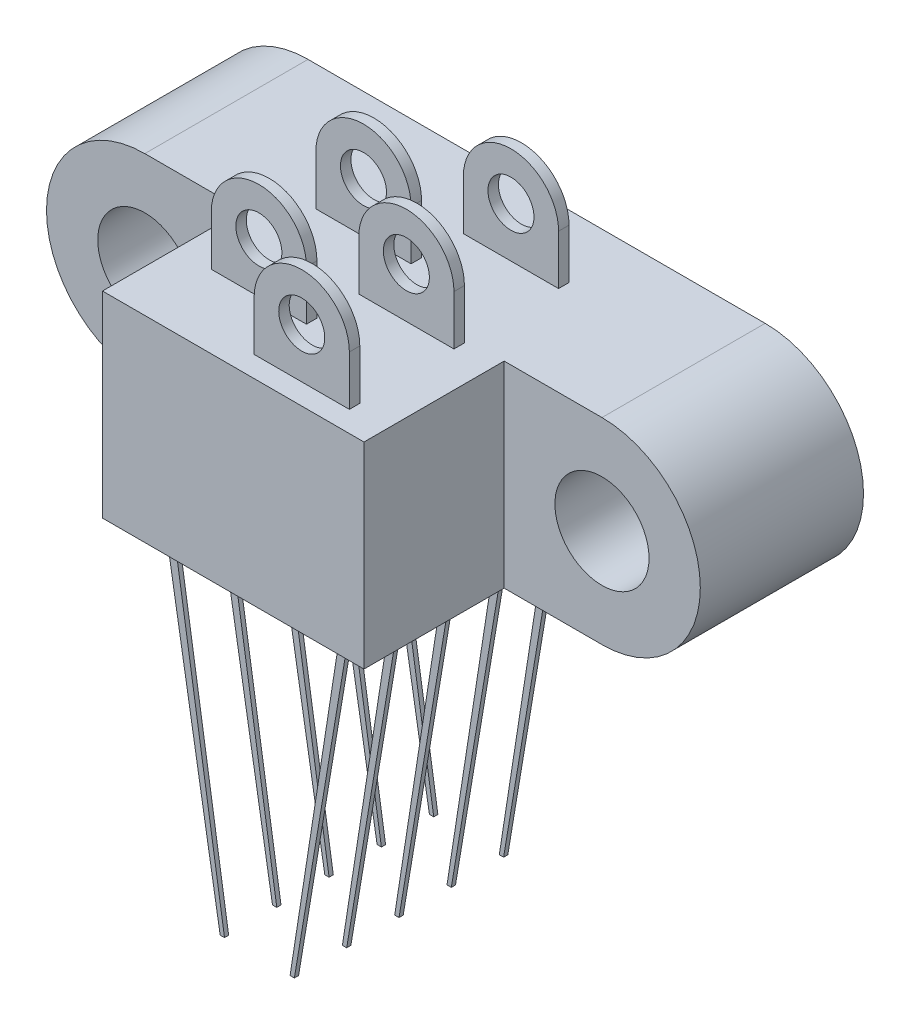
SolidWorks part; units mm, degrees
ref_plane "Front Plane" through (0, 0, 0) normal (0, 0, 1) x (1, 0, 0)
ref_plane "Top Plane" through (0, 0, 0) normal (0, 1, 0) x (1, 0, 0)
ref_plane "Right Plane" through (0, 0, 0) normal (1, 0, 0) x (0, 0, -1)
sketch "Sketch1" plane through (0, 0, 0) normal (0, 0, 1) x (1, 0, 0)
  line L0 (-5.5499, 2.3876) -> (5.5499, 2.3876)
  line L1 (-5.5499, -2.3876) -> (5.5499, -2.3876)
  circle A0 centre (-5.5499, 0) radius 1.143
  circle A1 centre (5.5499, 0) radius 1.143
  arc A2 (-5.5499, 2.3876) -> (-5.5499, -2.3876) centre (-5.5499, 0) ccw
  arc A3 (5.5499, -2.3876) -> (5.5499, 2.3876) centre (5.5499, 0) ccw
  dimension "D1" = 11.0998
  dimension "D2" = 5.5499
extrude "Boss-Extrude1" add sketch "Sketch1" along normal blind 3.9624
sketch "Sketch2" plane through (0, 0, 3.9624) normal (0, 0, 1) x (1, 0, 0)
  line L0 (0, 0) -> (0, 9.5761) construction
  line L1 (-3.175, 2.3876) -> (-3.175, -2.3876)
  line L2 (3.175, 2.3876) -> (3.175, -2.3876)
  line L3 (-3.175, 2.3876) -> (3.175, 2.3876)
  line L5 (-3.175, -2.3876) -> (3.175, -2.3876)
  dimension "D1" = 6.35
  dimension "D2" = 3.175
extrude "Boss-Extrude2" add sketch "Sketch2" along normal blind 3.4036
sketch3d "3DSketch1" plane through (0, 0, 0) normal (0, 0, 1) x (1, 0, 0)
  dimension "D1" = 1.651
  dimension "D2" = 1.27
  dimension "D3" = 2.54
  dimension "D4" = 3.81
  dimension "D5" = 5.08
sketch "Sketch3" plane through (0, 0, 1.651) normal (0, 0, -1) x (-1, 0, 0)
  line L0 (-1.1557, 4.7498) -> (-1.1557, 0.3247) construction
  line L1 (-5.5499, 2.3876) -> (5.5499, 2.3876) construction
  line L2 (0, 2.3876) -> (0, 3.5941) construction
  line L5 (-2.3114, 3.5941) -> (-2.3114, 2.3876)
  line L8 (0, 3.5941) -> (0, 2.3876)
  line L9 (0, 4.7845) -> (0, 9.569) construction
  line L11 (0, 2.3876) -> (-2.3114, 2.3876)
  arc A1 (0, 3.5941) -> (-2.3114, 3.5941) centre (-1.1557, 3.5941) ccw
  circle A2 centre (-1.1557, 3.5941) radius 0.5588
  dimension "D2" = 0
extrude "Boss-Extrude3" add sketch "Sketch3" along normal blind 0.127 and the other way blind 0.127
sketch "Sketch4" plane through (0, 0, 2.921) normal (0, 0, -1) x (-1, 0, 0)
  line L3 (0, 2.3876) -> (0, 3.5941) construction
  line L4 (2.3114, 3.5941) -> (2.3114, 2.3876)
  line L5 (2.3114, 2.3876) -> (0, 2.3876)
  line L6 (-2.3114, 3.5941) -> (-2.3114, 2.3876)
  line L7 (-2.3114, 2.3876) -> (0, 2.3876)
  line L8 (0, 2.3876) -> (0, 3.5941)
  line L9 (-2.3114, 3.5941) -> (-2.3114, 2.3876) construction
  line L10 (-2.3114, 2.3876) -> (2.3114, 2.3876) construction
  line L11 (0, 2.3876) -> (0, 3.5941)
  arc A2 (0, 3.5941) -> (-2.3114, 3.5941) centre (-1.1557, 3.5941) ccw
  arc A3 (0, 3.5941) -> (-2.3114, 3.5941) centre (-1.1557, 3.5941) ccw construction
  circle A4 centre (1.1557, 3.5941) radius 0.5588
  circle A5 centre (-1.1557, 3.5941) radius 0.5588
  circle A6 centre (-1.1557, 3.5941) radius 0.5588 construction
  arc A7 (0, 3.5941) -> (2.3114, 3.5941) centre (1.1557, 3.5941) cw
  dimension "D1" = 0
  dimension "D2" = 0
extrude "Boss-Extrude4" add sketch "Sketch4" along normal blind 0.127 and the other way blind 0.127
sketch "Sketch5" plane through (0, 0, 4.191) normal (0, 0, -1) x (-1, 0, 0)
  line L6 (-2.3114, 3.5941) -> (-2.3114, 2.3876)
  line L7 (-2.3114, 2.3876) -> (0, 2.3876)
  line L8 (0, 2.3876) -> (0, 3.5941)
  line L9 (-2.3114, 3.5941) -> (-2.3114, 2.3876)
  line L10 (-2.3114, 2.3876) -> (0, 2.3876)
  line L11 (0, 2.3876) -> (0, 3.5941)
  arc A2 (0, 3.5941) -> (-2.3114, 3.5941) centre (-1.1557, 3.5941) ccw
  arc A3 (0, 3.5941) -> (-2.3114, 3.5941) centre (-1.1557, 3.5941) ccw
  circle A5 centre (-1.1557, 3.5941) radius 0.5588
  circle A6 centre (-1.1557, 3.5941) radius 0.5588
  dimension "D1" = 0
  dimension "D2" = 0
sketch "Sketch6" plane through (0, 0, 6.731) normal (0, 0, -1) x (-1, 0, 0)
  line L15 (-2.3114, 3.5941) -> (-2.3114, 2.3876)
  line L16 (-2.3114, 2.3876) -> (0, 2.3876)
  line L17 (0, 2.3876) -> (0, 3.5941)
  line L18 (-2.3114, 3.5941) -> (-2.3114, 2.3876)
  line L19 (-2.3114, 2.3876) -> (0, 2.3876)
  line L20 (0, 2.3876) -> (0, 3.5941)
  arc A8 (0, 3.5941) -> (-2.3114, 3.5941) centre (-1.1557, 3.5941) ccw
  arc A9 (0, 3.5941) -> (-2.3114, 3.5941) centre (-1.1557, 3.5941) ccw
  circle A11 centre (-1.1557, 3.5941) radius 0.5588
  circle A12 centre (-1.1557, 3.5941) radius 0.5588
  dimension "D1" = 0
  dimension "D2" = 0
sketch "Sketch7" plane through (0, 0, 5.461) normal (0, 0, -1) x (-1, 0, 0)
  line L9 (2.3114, 2.3876) -> (2.3114, 3.5941)
  line L10 (0, 3.5941) -> (0, 2.3876)
  line L11 (0, 2.3876) -> (2.3114, 2.3876)
  line L12 (2.3114, 2.3876) -> (2.3114, 3.5941)
  line L13 (0, 3.5941) -> (0, 2.3876)
  line L14 (0, 2.3876) -> (2.3114, 2.3876)
  circle A3 centre (1.1557, 3.5941) radius 0.5588
  circle A4 centre (1.1557, 3.5941) radius 0.5588
  arc A6 (2.3114, 3.5941) -> (0, 3.5941) centre (1.1557, 3.5941) ccw
  arc A7 (2.3114, 3.5941) -> (0, 3.5941) centre (1.1557, 3.5941) ccw
  dimension "D1" = 0
  dimension "D2" = 0
extrude "Boss-Extrude5" add sketch "Sketch5" along normal blind 0.127 and the other way blind 0.127
extrude "Boss-Extrude6" add sketch "Sketch7" along normal blind 0.127 and the other way blind 0.127
extrude "Boss-Extrude7" add sketch "Sketch6" along normal blind 0.127 and the other way blind 0.127
sketch "Sketch8" plane through (0, 0, 1.651) normal (0, 0, -1) x (-1, 0, 0)
  line L0 (0, 0) -> (0, -17.2322) construction
  line L1 (5.5499, 0) -> (-5.5499, 0) construction
  line L2 (12.2116, -10.3124) -> (-12.586, -10.3124) construction
  line L3 (5.5499, -2.3876) -> (-5.5499, -2.3876) construction
  line L4 (2.2287, -2.3876) -> (2.0281, -2.3876)
  line L5 (-0.9009, -10.3124) -> (-0.7963, -10.3124)
  line L6 (2.2287, -2.3876) -> (0.9009, -10.3124)
  line L7 (0.9009, -10.3124) -> (0.7963, -10.3124) construction
  line L8 (2.0281, -2.3876) -> (0.7963, -10.3124)
  line L9 (-2.2287, -2.3876) -> (-2.0281, -2.3876)
  line L10 (-2.0281, -2.3876) -> (-0.7963, -10.3124)
  line L11 (-2.2287, -2.3876) -> (-0.9009, -10.3124)
  line L12 (0.9009, -10.3124) -> (0.7963, -10.3124)
  circle A0 centre (0, -8.7376) radius 1.0287 construction
  dimension "D1" = 8.7376
  dimension "D3" = 2.0574
  dimension "D2" = 10.3124
  dimension "D4" = 0
sketch "Sketch11" plane through (0, 0, 4.191) normal (0, 0, -1) x (-1, 0, 0)
  line L0 (0, 0) -> (0, -8.7532) construction
  line L1 (2.2287, -2.3876) -> (0.9009, -10.3124)
  line L2 (2.0281, -2.3876) -> (2.2287, -2.3876)
  line L3 (0.7963, -10.3124) -> (2.0281, -2.3876)
  line L4 (-0.9009, -10.3124) -> (-0.7963, -10.3124)
  line L5 (-0.9009, -10.3124) -> (-0.7963, -10.3124)
  line L6 (-0.7963, -10.3124) -> (-2.0281, -2.3876)
  line L7 (-0.7963, -10.3124) -> (-2.0281, -2.3876)
  line L8 (-2.0281, -2.3876) -> (-2.2287, -2.3876)
  line L9 (-2.0281, -2.3876) -> (-2.2287, -2.3876)
  line L10 (-2.2287, -2.3876) -> (-0.9009, -10.3124)
  line L11 (-2.2287, -2.3876) -> (-0.9009, -10.3124)
  line L12 (0.9009, -10.3124) -> (0.7963, -10.3124)
  dimension "D1" = 0
sketch "Sketch12" plane through (0, 0, 6.731) normal (0, 0, -1) x (-1, 0, 0)
  line L0 (0, 0) -> (0, -8.2673) construction
  line L1 (2.2287, -2.3876) -> (0.9009, -10.3124)
  line L2 (2.0281, -2.3876) -> (2.2287, -2.3876)
  line L3 (0.7963, -10.3124) -> (2.0281, -2.3876)
  line L4 (-0.9009, -10.3124) -> (-0.7963, -10.3124)
  line L5 (-0.9009, -10.3124) -> (-0.7963, -10.3124)
  line L6 (-0.7963, -10.3124) -> (-2.0281, -2.3876)
  line L7 (-0.7963, -10.3124) -> (-2.0281, -2.3876)
  line L8 (-2.0281, -2.3876) -> (-2.2287, -2.3876)
  line L9 (-2.0281, -2.3876) -> (-2.2287, -2.3876)
  line L10 (-2.2287, -2.3876) -> (-0.9009, -10.3124)
  line L11 (-2.2287, -2.3876) -> (-0.9009, -10.3124)
  line L12 (0.9009, -10.3124) -> (0.7963, -10.3124)
  dimension "D1" = 0
extrude "Boss-Extrude8" add sketch "Sketch8" along normal blind 0.0508 and the other way blind 0.0508
extrude "Boss-Extrude11" add sketch "Sketch11" along normal blind 0.0508 and the other way blind 0.0508
extrude "Boss-Extrude12" add sketch "Sketch12" along normal blind 0.0508 and the other way blind 0.0508
sketch "Sketch13" plane through (0, 0, 2.921) normal (0, 0, -1) x (-1, 0, 0)
  line L4 (0, 0) -> (0, -16.7259) construction
  line L5 (0.9009, -10.3124) -> (0.7963, -10.3124)
  line L6 (2.2287, -2.3876) -> (0.9009, -10.3124)
  line L7 (2.0281, -2.3876) -> (2.2287, -2.3876)
  line L8 (-0.9009, -10.3124) -> (-0.7963, -10.3124)
  line L9 (-0.7963, -10.3124) -> (-2.0281, -2.3876)
  line L10 (-2.0281, -2.3876) -> (-2.2287, -2.3876)
  line L11 (-2.2287, -2.3876) -> (-0.9009, -10.3124)
  line L12 (-0.9009, -10.3124) -> (-0.7963, -10.3124)
  line L13 (-0.7963, -10.3124) -> (-2.0281, -2.3876)
  line L14 (-2.0281, -2.3876) -> (-2.2287, -2.3876)
  line L15 (-2.2287, -2.3876) -> (-0.9009, -10.3124)
  line L16 (0.7963, -10.3124) -> (2.0281, -2.3876)
  point P2 (-0.8486, -10.3124)
  point P4 (0.8486, -10.3124)
  dimension "D1" = 0
extrude "Boss-Extrude13" add sketch "Sketch13" along normal blind 0.0508 and the other way blind 0.0508
sketch "Sketch15" plane through (0, 0, 5.461) normal (0, 0, -1) x (-1, 0, 0)
  line L0 (0, 0) -> (0, -7.9203) construction
  line L1 (-0.9009, -10.3124) -> (-2.2287, -2.3876)
  line L2 (-2.2287, -2.3876) -> (-2.0281, -2.3876)
  line L3 (-2.0281, -2.3876) -> (-0.7963, -10.3124)
  line L4 (-0.7963, -10.3124) -> (-0.9009, -10.3124)
  line L8 (0.7963, -10.3124) -> (0.9009, -10.3124)
  line L9 (2.0281, -2.3876) -> (0.7963, -10.3124)
  line L10 (2.2287, -2.3876) -> (2.0281, -2.3876)
  line L11 (0.9009, -10.3124) -> (2.2287, -2.3876)
  line L12 (0.7963, -10.3124) -> (0.9009, -10.3124)
  line L13 (2.0281, -2.3876) -> (0.7963, -10.3124)
  line L14 (2.2287, -2.3876) -> (2.0281, -2.3876)
  line L15 (0.9009, -10.3124) -> (2.2287, -2.3876)
  dimension "D1" = 0
extrude "Boss-Extrude14" add sketch "Sketch15" along normal blind 0.0508 and the other way blind 0.0508
